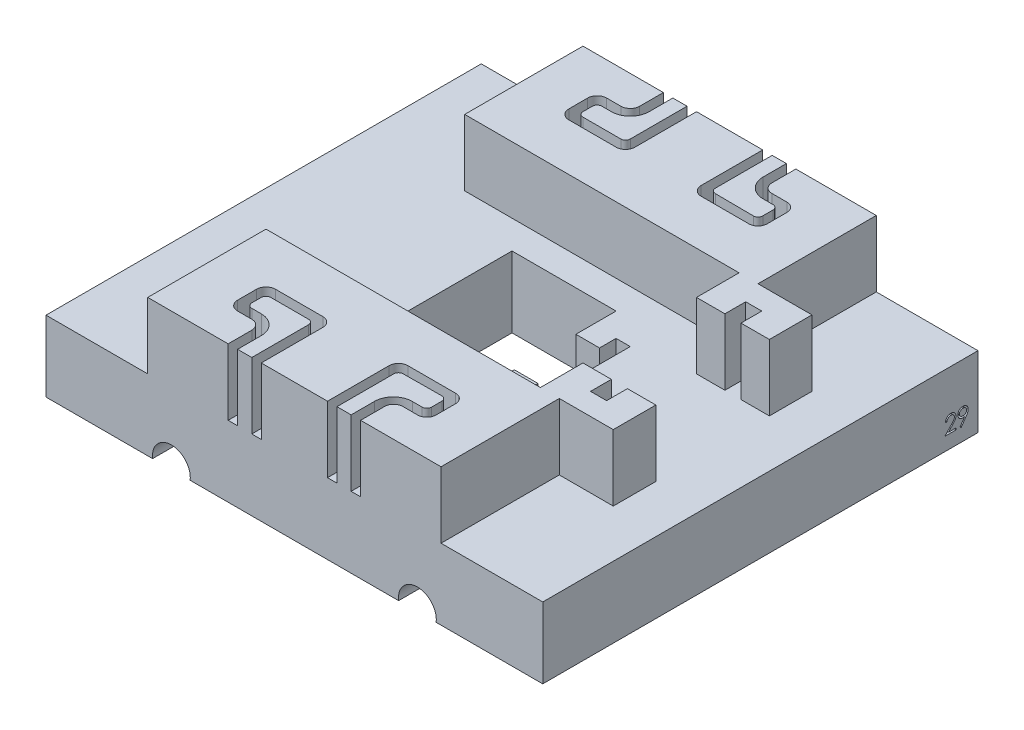
SolidWorks part; units mm, degrees
ref_plane "Front Plane" through (0, 0, 0) normal (0, 0, 1) x (1, 0, 0)
ref_plane "Top Plane" through (0, 0, 0) normal (0, 1, 0) x (1, 0, 0)
ref_plane "Right Plane" through (0, 0, 0) normal (1, 0, 0) x (0, 0, -1)
sketch "Sketch1" plane through (0, 0, 0) normal (0, 1, 0) x (1, 0, 0)
  line L1 (0, 0) -> (105, 0)
  line L2 (0, 0) -> (0, 92)
  line L3 (0, 92) -> (105, 92)
  line L4 (105, 0) -> (105, 92)
  dimension "D1" = 92
  dimension "D2" = 105
extrude "Boss-Extrude1" add sketch "Sketch1" along normal blind 15
sketch "Sketch2" plane through (0, 15, 0) normal (0, 1, 0) x (1, 0, 0)
  line L0 (0, 46) -> (105, 46) construction
  line L1 (0, 92) -> (0, 0) construction
  line L2 (105, 0) -> (105, 92) construction
  line L3 (52.5, 0) -> (52.5, 92) construction
  line L4 (0, 0) -> (105, 0) construction
  line L5 (105, 92) -> (0, 92) construction
  line L7 (67.5, 31) -> (37.5, 31)
  line L8 (67.5, 31) -> (67.5, 61)
  line L9 (67.5, 61) -> (37.5, 61)
  line L10 (37.5, 31) -> (37.5, 61)
  line L11 (67.5, 31) -> (37.5, 61) construction
  line L12 (67.5, 61) -> (37.5, 31) construction
  point P12 (52.5, 46)
  dimension "D1" = 30
  dimension "D2" = 30
extrude "Cut-Extrude1" cut sketch "Sketch2" against normal blind 72
ref_plane "Plane5" through (52.5, 0, 0) normal (-1, 0, 0) x (0, 0, 1)
ref_plane "Plane6" through (26.25, 0, 0) normal (-1, 0, 0) x (0, 0, 1)
ref_plane "Plane7" through (78.75, 0, 0) normal (-1, 0, 0) x (0, 0, 1)
ref_plane "Plane8" through (0, 0, -46) normal (0, 0, 1) x (1, 0, 0)
sketch "Sketch15" plane through (0, 15, 0) normal (0, 1, 0) x (1, 0, 0)
  line L0 (0, 46) -> (105, 46) construction
  line L1 (0, 92) -> (0, 0) construction
  line L2 (105, 0) -> (105, 92) construction
  line L4 (72.5, 67) -> (72.5, 46)
  line L5 (72.5, 46) -> (72.5, 25)
  line L7 (72.5, 67) -> (59.5, 67)
  line L8 (67.5, 61) -> (37.5, 61) construction
  line L9 (59.5, 61) -> (59.5, 52.5)
  line L10 (59.5, 52.5) -> (64.5, 52.5)
  line L11 (64.5, 52.5) -> (64.5, 56)
  line L12 (64.5, 56) -> (67.5, 56)
  line L13 (67.5, 31) -> (67.5, 61) construction
  line L15 (67.5, 36) -> (64.5, 36)
  line L16 (64.5, 36) -> (64.5, 39.5)
  line L17 (64.5, 39.5) -> (59.5, 39.5)
  line L18 (59.5, 39.5) -> (59.5, 31)
  line L19 (37.5, 31) -> (67.5, 31) construction
  line L21 (59.5, 67) -> (59.5, 61)
  line L22 (59.5, 31) -> (59.5, 25)
  line L23 (59.5, 25) -> (72.5, 25)
  line L25 (67.5, 56) -> (67.5, 46)
  line L26 (67.5, 46) -> (67.5, 36)
  dimension "D1" = 21
  dimension "D2" = 21
  dimension "D3" = 3
  dimension "D4" = 3
  dimension "D5" = 13
  dimension "D6" = 13
  dimension "D7" = 10
  dimension "D8" = 10
  dimension "D9" = 5
  dimension "D10" = 6.5
  dimension "D11" = 6.5
extrude "Boss-Extrude4" add sketch "Sketch15" against normal blind 15
sketch "Sketch18" plane through (0, 0, -46) normal (0, 0, 1) x (1, 0, 0)
  line L0 (52.5, 0.5) -> (52.5, 0) construction
  line L2 (37.5, 0) -> (59.5, 0) construction
  line L3 (0, 0.5) -> (74.5, 0.5) construction
  line L4 (52.5, 0) -> (52.5, 15) construction
  line L5 (0, 15) -> (105, 15) construction
  line L6 (105, 0) -> (0, 0) construction
  circle A0 centre (26.5, 0.5) radius 4
  circle A2 centre (78.5, 0.5) radius 4
  dimension "D2" = 8
  dimension "D4" = 8
  dimension "D1" = 0.5
  dimension "D3" = 26
  dimension "D5" = 26
extrude "Cut-Extrude2" cut sketch "Sketch18" against normal blind 64 and the other way blind 84
sketch "Sketch22" plane through (0, 0, -46) normal (0, 0, 1) x (1, 0, 0)
  circle A0 centre (26.5, 0.5) radius 6
  dimension "D1" = 12
extrude "Cut-Extrude3" cut sketch "Sketch22" against normal blind 10 and the other way blind 10
ref_plane "Plane9" through (0, 0, -69) normal (0, 0, -1) x (-1, 0, 0)
sketch "Sketch23" plane through (0, 0, -69) normal (0, 0, -1) x (-1, 0, 0)
  circle A0 centre (-78.5, 0.5) radius 6
  dimension "D1" = 12
extrude "Cut-Extrude4" cut sketch "Sketch23" against normal blind 10 and the other way blind 10
ref_plane "Plane10" through (0, 0, -23) normal (0, 0, 1) x (1, 0, 0)
sketch "Sketch24" plane through (0, 0, -23) normal (0, 0, 1) x (1, 0, 0)
  circle A0 centre (78.5, 0.5) radius 6
  dimension "D1" = 12
extrude "Cut-Extrude5" cut sketch "Sketch24" against normal blind 10 and the other way blind 10
sketch "Sketch27" plane through (0, 0, 0) normal (-1, 0, 0) x (0, 0, 1)
  text T0 "29"
extrude "Cut-Extrude7" cut sketch "Sketch27" against normal blind 2
sketch "Sketch28" plane through (105, 0, 0) normal (1, 0, 0) x (0, 0, -1)
  text T0 "29"
extrude "Cut-Extrude8" cut sketch "Sketch28" against normal blind 2
sketch "Sketch29" plane through (0, 15, 0) normal (0, 1, 0) x (1, 0, 0)
  line L0 (0, 46) -> (105, 46) construction
  line L1 (40.5, 0) -> (43.5, 0)
  line L2 (52.5, 92) -> (52.5, 0) construction
  line L3 (105, 92) -> (0, 92) construction
  line L4 (0, 0) -> (105, 0) construction
  line L5 (0, 92) -> (0, 0) construction
  line L6 (105, 0) -> (105, 92) construction
  line L7 (52.5, 25) -> (21.5, 25)
  line L8 (21.5, 25) -> (21.5, 0)
  line L9 (21.5, 0) -> (38.5, 0)
  line L10 (83.5, 0) -> (83.5, 25)
  line L11 (79.5, 25) -> (52.5, 25)
  line L12 (45.5, 0) -> (45.5, 13)
  line L13 (43.5, 15) -> (33.5, 15)
  line L14 (31.5, 13) -> (31.5, 9)
  line L15 (33.5, 7) -> (36.5, 7)
  line L16 (38.5, 5) -> (38.5, 0)
  line L17 (43.5, 0) -> (43.5, 12)
  line L18 (42.5, 13) -> (34.5, 13)
  line L19 (33.5, 12) -> (33.5, 10)
  line L20 (34.5, 9) -> (36.5, 9)
  line L21 (40.5, 5) -> (40.5, 0)
  line L22 (45.5, 0) -> (59.5, 0)
  line L23 (59.5, 0) -> (59.5, 13)
  line L24 (61.5, 15) -> (71.58, 15)
  line L25 (73.5, 13.08) -> (73.5, 8.92)
  line L26 (71.58, 7) -> (68.42, 7)
  line L27 (66.5, 5.08) -> (66.5, 0)
  line L28 (61.5, 0) -> (61.5, 12.0079)
  line L29 (62.4921, 13.0079) -> (70.572, 13.072)
  line L30 (71.58, 12.072) -> (71.58, 9.92)
  line L31 (70.58, 8.92) -> (68.5, 8.92)
  line L32 (64.5, 4.92) -> (64.5, 0)
  line L33 (61.5, 0) -> (64.5, 0)
  line L34 (66.5, 0) -> (83.5, 0)
  line L35 (79.5, 25) -> (79.5, 34)
  line L36 (79.5, 34) -> (85.5, 34)
  line L37 (94.9, 34) -> (94.9, 25)
  line L38 (94.9, 25) -> (83.5, 25)
  line L39 (85.5, 34) -> (85.5, 29.6)
  line L40 (85.5, 29.6) -> (88.9, 29.6)
  line L41 (88.9, 29.6) -> (88.9, 34)
  line L42 (88.9, 34) -> (94.9, 34)
  line L43 (88.9, 58) -> (94.9, 58)
  line L44 (88.9, 62.4) -> (88.9, 58)
  line L45 (85.5, 62.4) -> (88.9, 62.4)
  line L46 (85.5, 58) -> (85.5, 62.4)
  line L47 (94.9, 67) -> (83.5, 67)
  line L48 (94.9, 58) -> (94.9, 67)
  line L49 (79.5, 58) -> (85.5, 58)
  line L50 (79.5, 67) -> (79.5, 58)
  line L51 (66.5, 92) -> (83.5, 92)
  line L52 (61.5, 92) -> (64.5, 92)
  line L53 (64.5, 87.08) -> (64.5, 92)
  line L54 (70.58, 83.08) -> (68.5, 83.08)
  line L55 (71.58, 79.928) -> (71.58, 82.08)
  line L56 (62.4921, 78.9921) -> (70.572, 78.928)
  line L57 (61.5, 92) -> (61.5, 79.9921)
  line L58 (66.5, 86.92) -> (66.5, 92)
  line L59 (71.58, 85) -> (68.42, 85)
  line L60 (73.5, 78.92) -> (73.5, 83.08)
  line L61 (61.5, 77) -> (71.58, 77)
  line L62 (59.5, 92) -> (59.5, 79)
  line L63 (45.5, 92) -> (59.5, 92)
  line L64 (40.5, 87) -> (40.5, 92)
  line L65 (34.5, 83) -> (36.5, 83)
  line L66 (33.5, 80) -> (33.5, 82)
  line L67 (42.5, 79) -> (34.5, 79)
  line L68 (43.5, 92) -> (43.5, 80)
  line L69 (38.5, 87) -> (38.5, 92)
  line L70 (33.5, 85) -> (36.5, 85)
  line L71 (31.5, 79) -> (31.5, 83)
  line L72 (43.5, 77) -> (33.5, 77)
  line L73 (45.5, 92) -> (45.5, 79)
  line L74 (79.5, 67) -> (52.5, 67)
  line L75 (83.5, 92) -> (83.5, 67)
  line L76 (21.5, 92) -> (38.5, 92)
  line L77 (21.5, 67) -> (21.5, 92)
  line L78 (52.5, 67) -> (21.5, 67)
  line L79 (40.5, 92) -> (43.5, 92)
  arc A0 (45.5, 13) -> (43.5, 15) centre (43.5, 13) ccw
  arc A1 (38.5, 5) -> (36.5, 7) centre (36.5, 5) ccw
  arc A2 (31.5, 9) -> (33.5, 7) centre (33.5, 9) ccw
  arc A3 (31.5, 13) -> (33.5, 15) centre (33.5, 13) cw
  arc A4 (33.5, 10) -> (34.5, 9) centre (34.5, 10) ccw
  arc A5 (33.5, 12) -> (34.5, 13) centre (34.5, 12) cw
  arc A6 (42.5, 13) -> (43.5, 12) centre (42.5, 12) cw
  arc A7 (40.5, 5) -> (36.5, 9) centre (36.5, 5) ccw
  arc A8 (61.5, 15) -> (59.5, 13) centre (61.5, 13) ccw
  arc A9 (68.42, 7) -> (66.5, 5.08) centre (68.42, 5.08) ccw
  arc A10 (73.5, 8.92) -> (71.58, 7) centre (71.58, 8.92) cw
  arc A11 (73.5, 13.08) -> (71.58, 15) centre (71.58, 13.08) ccw
  arc A12 (62.4921, 13.0079) -> (61.5, 12.0079) centre (62.5, 12.0079) ccw
  arc A13 (71.58, 9.92) -> (70.58, 8.92) centre (70.58, 9.92) cw
  arc A14 (71.58, 12.072) -> (70.572, 13.072) centre (70.58, 12.072) ccw
  arc A15 (64.5, 4.92) -> (68.5, 8.92) centre (68.5, 4.92) cw
  arc A16 (64.5, 87.08) -> (68.5, 83.08) centre (68.5, 87.08) ccw
  arc A17 (71.58, 79.928) -> (70.572, 78.928) centre (70.58, 79.928) cw
  arc A18 (71.58, 82.08) -> (70.58, 83.08) centre (70.58, 82.08) ccw
  arc A19 (62.4921, 78.9921) -> (61.5, 79.9921) centre (62.5, 79.9921) cw
  arc A20 (73.5, 78.92) -> (71.58, 77) centre (71.58, 78.92) cw
  arc A21 (73.5, 83.08) -> (71.58, 85) centre (71.58, 83.08) ccw
  arc A22 (68.42, 85) -> (66.5, 86.92) centre (68.42, 86.92) cw
  arc A23 (61.5, 77) -> (59.5, 79) centre (61.5, 79) cw
  arc A24 (40.5, 87) -> (36.5, 83) centre (36.5, 87) cw
  arc A25 (42.5, 79) -> (43.5, 80) centre (42.5, 80) ccw
  arc A26 (33.5, 80) -> (34.5, 79) centre (34.5, 80) ccw
  arc A27 (33.5, 82) -> (34.5, 83) centre (34.5, 82) cw
  arc A28 (31.5, 79) -> (33.5, 77) centre (33.5, 79) ccw
  arc A29 (31.5, 83) -> (33.5, 85) centre (33.5, 83) cw
  arc A30 (38.5, 87) -> (36.5, 85) centre (36.5, 87) cw
  arc A31 (45.5, 79) -> (43.5, 77) centre (43.5, 79) cw
  point P31 (45.5, 15)
  point P34 (38.5, 7)
  point P37 (31.5, 7)
  point P40 (31.5, 15)
  point P57 (59.5, 15)
  point P60 (66.5, 7)
  point P63 (73.5, 7)
  point P66 (73.5, 15)
  point P157 (73.5, 77)
  point P158 (73.5, 85)
  point P159 (66.5, 85)
  point P160 (59.5, 77)
  point P161 (31.5, 77)
  point P162 (31.5, 85)
  point P163 (38.5, 85)
  point P164 (45.5, 77)
  dimension "D14" = 2
  dimension "D15" = 2
  dimension "D16" = 1
  dimension "D17" = 4
  dimension "D23" = 2
  dimension "D24" = 1.92
  dimension "D25" = 1
  dimension "D26" = 1
  dimension "D27" = 4
  dimension "D1" = 31
  dimension "D2" = 31
  dimension "D3" = 25
  dimension "D4" = 15
  dimension "D5" = 14
  dimension "D6" = 8
  dimension "D7" = 7
  dimension "D8" = 2
  dimension "D9" = 2
  dimension "D10" = 2
  dimension "D11" = 2
  dimension "D12" = 2
  dimension "D13" = 7
  dimension "D18" = 15
  dimension "D19" = 7
  dimension "D20" = 14
  dimension "D21" = 8
  dimension "D22" = 7
  dimension "D28" = 2
  dimension "D29" = 9
  dimension "D30" = 15.4
  dimension "D31" = 6
  dimension "D32" = 6
  dimension "D33" = 4
  dimension "D34" = 25
  dimension "D35" = 4.4
extrude "Boss-Extrude5" add sketch "Sketch29" along normal blind 14
